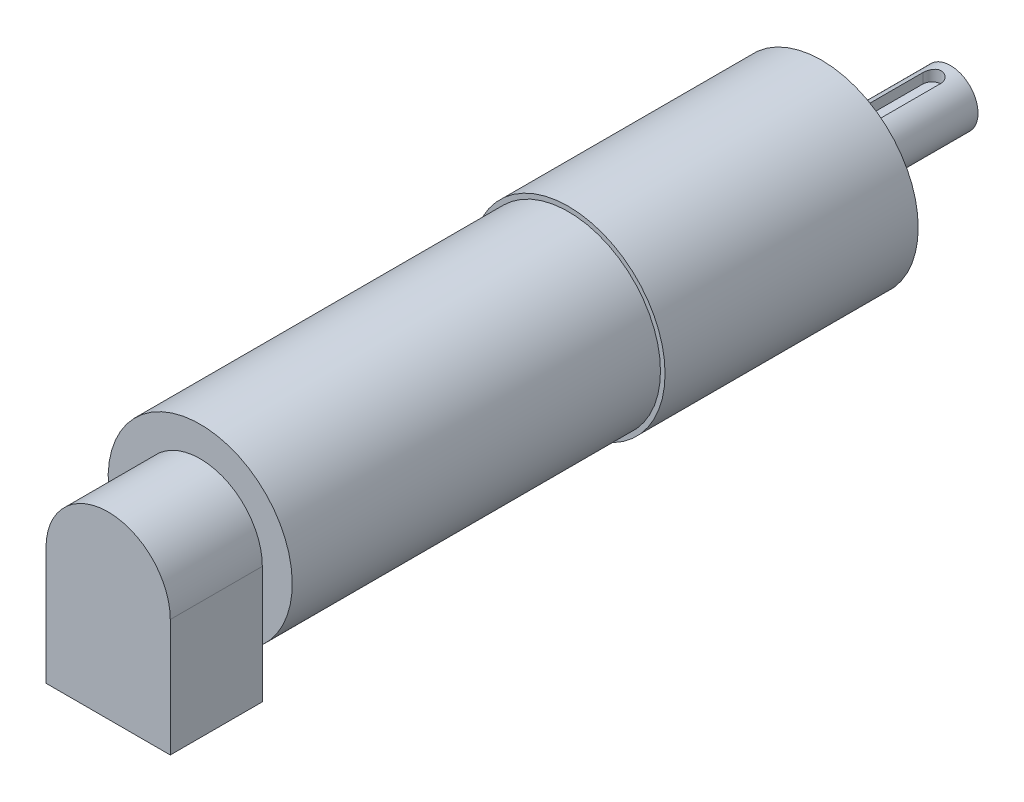
SolidWorks part; units mm, degrees
ref_plane "前视基准面" through (0, 0, 0) normal (0, 0, 1) x (1, 0, 0)
ref_plane "上视基准面" through (0, 0, 0) normal (0, 1, 0) x (1, 0, 0)
ref_plane "右视基准面" through (0, 0, 0) normal (1, 0, 0) x (0, 0, -1)
other "re40"
sketch "草图1" plane through (0, 0, 0) normal (0, 0, 1) x (1, 0, 0)
  circle A0 centre (0, 0) radius 21
  dimension "D1" = 42
extrude "齿轮箱" add sketch "草图1" along normal blind 55
sketch "草图2" plane through (0, 0, 55) normal (0, 0, 1) x (1, 0, 0)
  circle A0 centre (0, 0) radius 20
  dimension "D1" = 40
extrude "电机" add sketch "草图2" along normal blind 80
sketch "草图3" plane through (0, 0, 135) normal (0, 0, 1) x (1, 0, 0)
  line L0 (0, 0) -> (0, -42.2314) construction
  line L1 (-13.5, 0) -> (13.5, 0) construction
  line L3 (-13.5, -25.5) -> (13.5, -25.5)
  line L4 (-13.5, -25.5) -> (-13.5, 0)
  line L6 (13.5, -25.5) -> (13.5, 0)
  line L7 (-13.5, -25.5) -> (13.5, 0) construction
  line L8 (-13.5, 0) -> (13.5, -25.5) construction
  arc A1 (13.5, 0) -> (-13.5, 0) centre (0, 0) ccw
  point P2 (0, -12.75)
  point P5 (0, 13.5)
  dimension "D1" = 13.5
  dimension "D2" = 39
extrude "编码盘" add sketch "草图3" along normal blind 20
sketch "草图5" plane through (0, 0, 0) normal (0, 0, -1) x (-1, 0, 0)
  circle A0 centre (0, 0) radius 14
  dimension "D1" = 28
extrude "轴承" add sketch "草图5" along normal blind 3
sketch "草图4" plane through (0, 0, -3) normal (0, 0, -1) x (-1, 0, 0)
  circle A0 centre (0, 0) radius 6
  dimension "D1" = 12
extrude "轴" add sketch "草图4" along normal blind 25 separate body
ref_plane "基准面1" through (0, 6, 0) normal (0, 1, 0) x (-1, 0, 0)
sketch "草图6" plane through (0, 6, 0) normal (0, 1, 0) x (-1, 0, 0)
  line L0 (0, 0) -> (0, -29.9259) construction
  line L1 (0, -24) -> (0, -8) construction
  line L2 (-2, -24) -> (-2, -8)
  line L3 (2, -24) -> (2, -8)
  line L4 (-6, -28) -> (6, -28) construction
  arc A0 (-2, -24) -> (2, -24) centre (0, -24) ccw
  arc A1 (2, -8) -> (-2, -8) centre (0, -8) ccw
  point P5 (0, -16)
  dimension "D1" = 4
  dimension "D3" = 16
  dimension "D2" = 4
extrude "切除-拉伸1" cut sketch "草图6" against normal blind 2.5
hole_wizard "M4 螺纹孔1" positions "草图8" profile "草图7" tap size "M4" standard "GB"
sketch "草图8" plane through (0, 0, 0) normal (0, 0, -1) x (-1, 0, 0)
  circle A0 centre (0, 0) radius 17.5 construction
  point P0 (0, 17.5)
  point P10 (17.5, 0)
  point P11 (0, -17.5)
  point P12 (-17.5, 0)
  dimension "D1" = 35
  dimension "D2" = 4
sketch "草图7" plane through (0, 17.5, 0) normal (1, 0, 0) x (0, 1, 0)
  line L0 (0, 0) -> (0, 6.9914)
  line L1 (0, 6.9914) -> (1.65, 6)
  line L2 (1.65, 6) -> (1.65, 0)
  line L5 (1.65, 0) -> (0, 0)
  line L10 (0, 6.9914) -> (-1.65, 6) construction
  line L11 (0, -6.35) -> (0, 107.95) construction
  dimension "螺纹孔钻头直径" = 3.3
  dimension "螺纹孔钻头深度" = 6
  dimension "导头角度" = 118
cosmetic thread "孔螺蚊线1" parameters "D1"=4.3, "D2"=4
cosmetic thread "孔螺蚊线2" parameters "D1"=4.3, "D2"=4
cosmetic thread "孔螺蚊线3" parameters "D1"=4.3, "D2"=4
cosmetic thread "孔螺蚊线4" parameters "D1"=4.3, "D2"=4
